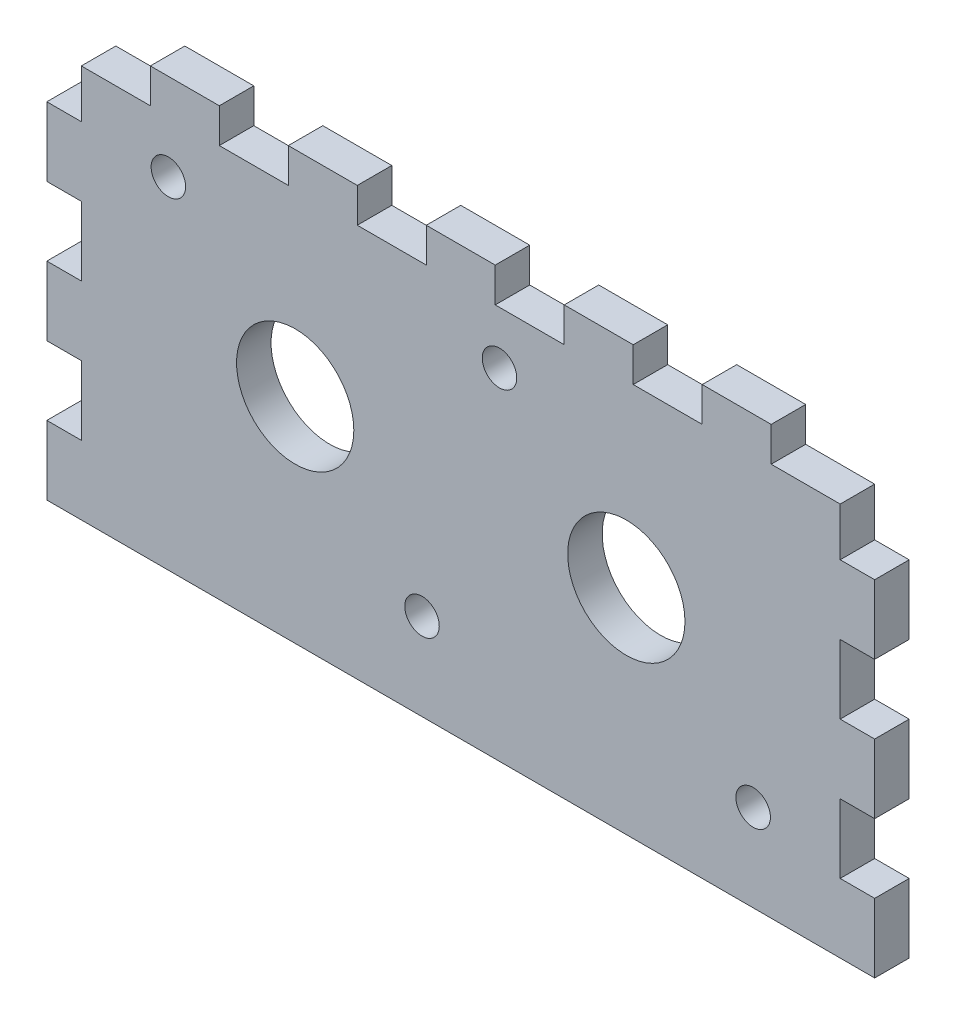
SolidWorks part; units mm, degrees
ref_plane "정면" through (0, 0, 0) normal (0, 0, 1) x (1, 0, 0)
ref_plane "윗면" through (0, 0, 0) normal (0, 1, 0) x (1, 0, 0)
ref_plane "우측면" through (0, 0, 0) normal (1, 0, 0) x (0, 0, -1)
sketch "스케치1" plane through (0, 0, 0) normal (0, 0, 1) x (1, 0, 0)
  line L0 (-24, 31.6233) -> (-24, -26.8484) construction
  line L1 (-55, 28.5) -> (55, 28.5)
  line L2 (-55, 28.5) -> (-55, -28.5)
  line L3 (-55, -28.5) -> (55, -28.5)
  line L4 (55, 28.5) -> (55, -28.5)
  line L5 (-55, 28.5) -> (55, -28.5) construction
  line L6 (-55, -28.5) -> (55, 28.5) construction
  line L7 (-53.6978, 32.1978) -> (6.8397, -28.3397) construction
  line L8 (0, 30.5742) -> (0, -34.7431) construction
  line L9 (24, 33.0742) -> (24, -28.3397) construction
  line L10 (0.2032, 26.2968) -> (53.7596, -27.2596) construction
  circle A0 centre (24, 2.5) radius 8.5
  circle A1 centre (-24, 2.5) radius 8.5
  circle A2 centre (-42.3848, 20.8848) radius 2.5
  circle A3 centre (-5.6152, -15.8848) radius 2.5
  circle A4 centre (5.6152, 20.8848) radius 2.5
  circle A5 centre (42.3848, -15.8848) radius 2.5
  point P0 (0, 0)
  dimension "D3" = 17
  dimension "D9" = 5
  dimension "D10" = 26
  dimension "D13" = 5
  dimension "D14" = 26
  dimension "D1" = 57
  dimension "D2" = 110
  dimension "D4" = 31
  dimension "D5" = 31
  dimension "D6" = 26
  dimension "D7" = 26
  dimension "D8" = 45
  dimension "D11" = 26
  dimension "D12" = 45
  dimension "D15" = 26
extrude "보스-돌출1" add sketch "스케치1" along normal blind 5
sketch "스케치2" plane through (0, 0, 5) normal (0, 0, 1) x (1, 0, 0)
  line L1 (55, -28.5) -> (60, -28.5)
  line L2 (55, -28.5) -> (55, -18.5)
  line L3 (55, -18.5) -> (60, -18.5)
  line L4 (60, -28.5) -> (60, -18.5)
  dimension "D1" = 5
  dimension "D2" = 10
extrude "보스-돌출2" add sketch "스케치2" against normal up to surface (5 mm away) up to face at (0, 0, 0)
pattern_linear "선형 패턴1" count 3 spacing 20 along (0, 1, 0) of "보스-돌출2"
mirror "대칭 복사1" about plane through (0, 0, 0) normal (1, 0, 0) of "선형 패턴1", "보스-돌출2"
sketch "스케치3" plane through (0, 0, 5) normal (0, 0, 1) x (1, 0, 0)
  line L0 (55, 28.5) -> (-55, 28.5) construction
  line L1 (-5, 28.5) -> (5, 28.5)
  line L2 (-5, 28.5) -> (-5, 33.5)
  line L3 (-5, 33.5) -> (5, 33.5)
  line L4 (5, 28.5) -> (5, 33.5)
  point P6 (0, 33.5)
  point P7 (0, 28.5)
  dimension "D1" = 5
  dimension "D2" = 10
extrude "보스-돌출3" add sketch "스케치3" against normal up to surface (5 mm away) up to face at (0, 1.25, 0)
pattern_linear "선형 패턴2" count 3 spacing 20 along (1, 0, 0) of "보스-돌출3"
pattern_linear "선형 패턴3" count 3 spacing 20 along (-1, 0, 0) of "보스-돌출3"
